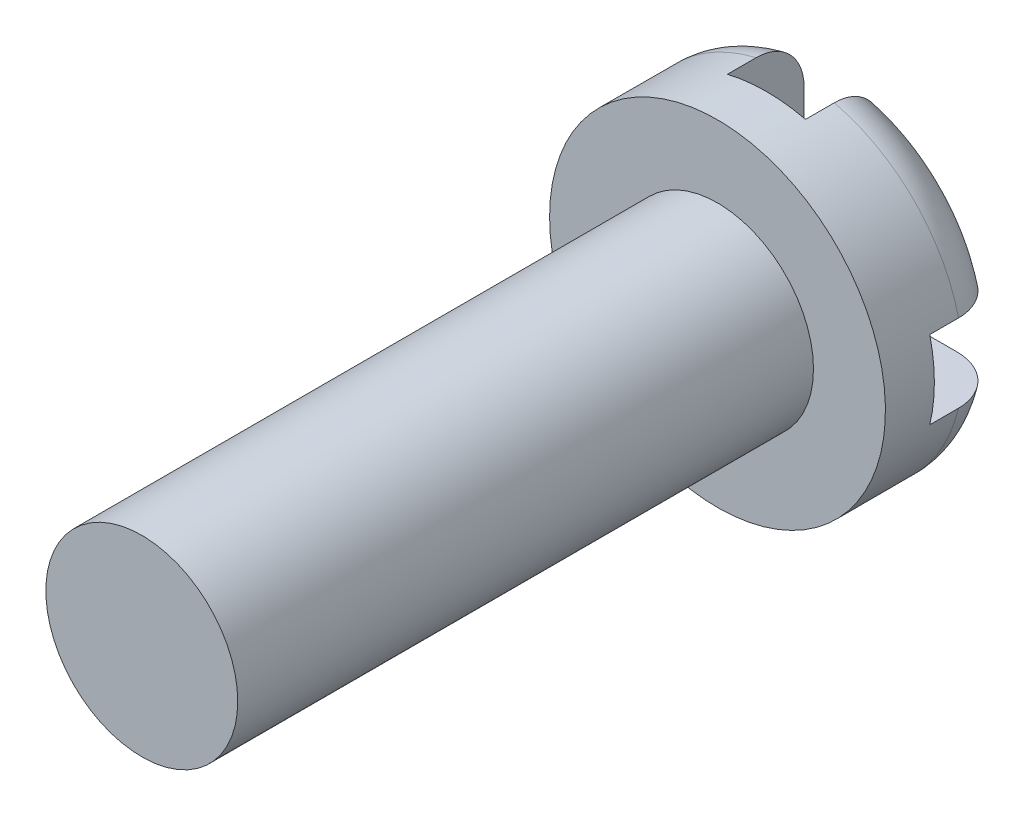
SolidWorks part; units mm, degrees
ref_plane "前视基准面" through (0, 0, 0) normal (0, 0, 1) x (1, 0, 0)
ref_plane "上视基准面" through (0, 0, 0) normal (0, 1, 0) x (1, 0, 0)
ref_plane "右视基准面" through (0, 0, 0) normal (1, 0, 0) x (0, 0, -1)
sketch "草图1" plane through (0, 0, 0) normal (0, 0, 1) x (1, 0, 0)
  circle A0 centre (0, 0) radius 1
extrude "凸台-拉伸1" add sketch "草图1" along normal blind 6
sketch "草图2" plane through (0, 0, 0) normal (0, 0, -1) x (-1, 0, 0)
  circle A0 centre (0, 0) radius 1.75
  dimension "D1" = 3.5
extrude "凸台-拉伸2" add sketch "草图2" along normal blind 1.31
fillet "圆角1" radius 0.5 1 edges at (-1.75, 0, -1.31)
sketch "草图3" plane through (0, 0, -1.31) normal (0, 0, -1) x (-1, 0, 0)
  line L0 (-0.7071, 0.7071) -> (-0.7071, 6.0064) construction
  line L1 (1, -1) -> (-1, -1) construction
  line L2 (1, -1) -> (1, 1) construction
  line L3 (1, 1) -> (-1, 1) construction
  line L4 (-1, -1) -> (-1, 1) construction
  line L5 (1, -1) -> (-1, 1) construction
  line L6 (1, 1) -> (-1, -1) construction
  line L7 (0.7071, 0.7071) -> (0.7071, 6.0064) construction
  line L8 (0.7071, 6.0064) -> (-0.7071, 6.0064) construction
  line L9 (0.7071, 0.7071) -> (6.0064, 0.7071) construction
  line L10 (0.7071, -0.7071) -> (6.0064, -0.7071) construction
  line L11 (6.0064, -0.7071) -> (6.0064, 0.7071) construction
  line L12 (0.7071, -0.7071) -> (0.7071, -6.0064) construction
  line L13 (-0.7071, -0.7071) -> (-0.7071, -6.0064) construction
  line L14 (-0.7071, -6.0064) -> (0.7071, -6.0064) construction
  line L15 (-0.7071, -0.7071) -> (-6.0064, -0.7071) construction
  line L16 (-0.7071, 0.7071) -> (-6.0064, 0.7071) construction
  line L17 (-6.0064, 0.7071) -> (-6.0064, -0.7071) construction
  line L18 (0.4071, 0.4071) -> (0.4071, 5.7064)
  line L19 (0.4071, 5.7064) -> (-0.4071, 5.7064)
  line L20 (-0.4071, 0.4071) -> (-0.4071, 5.7064)
  line L21 (-0.4071, 0.4071) -> (-5.7064, 0.4071)
  line L22 (-5.7064, 0.4071) -> (-5.7064, -0.4071)
  line L23 (-0.4071, -0.4071) -> (-5.7064, -0.4071)
  line L24 (-0.4071, -0.4071) -> (-0.4071, -5.7064)
  line L25 (-0.4071, -5.7064) -> (0.4071, -5.7064)
  line L26 (0.4071, -0.4071) -> (0.4071, -5.7064)
  line L27 (0.4071, -0.4071) -> (5.7064, -0.4071)
  line L28 (5.7064, -0.4071) -> (5.7064, 0.4071)
  line L29 (0.4071, 0.4071) -> (5.7064, 0.4071)
  circle A0 centre (0, 0) radius 1 construction
  dimension "D1" = 4
  dimension "D2" = 0.3
extrude "切除-拉伸1" cut sketch "草图3" against normal blind 0.8
